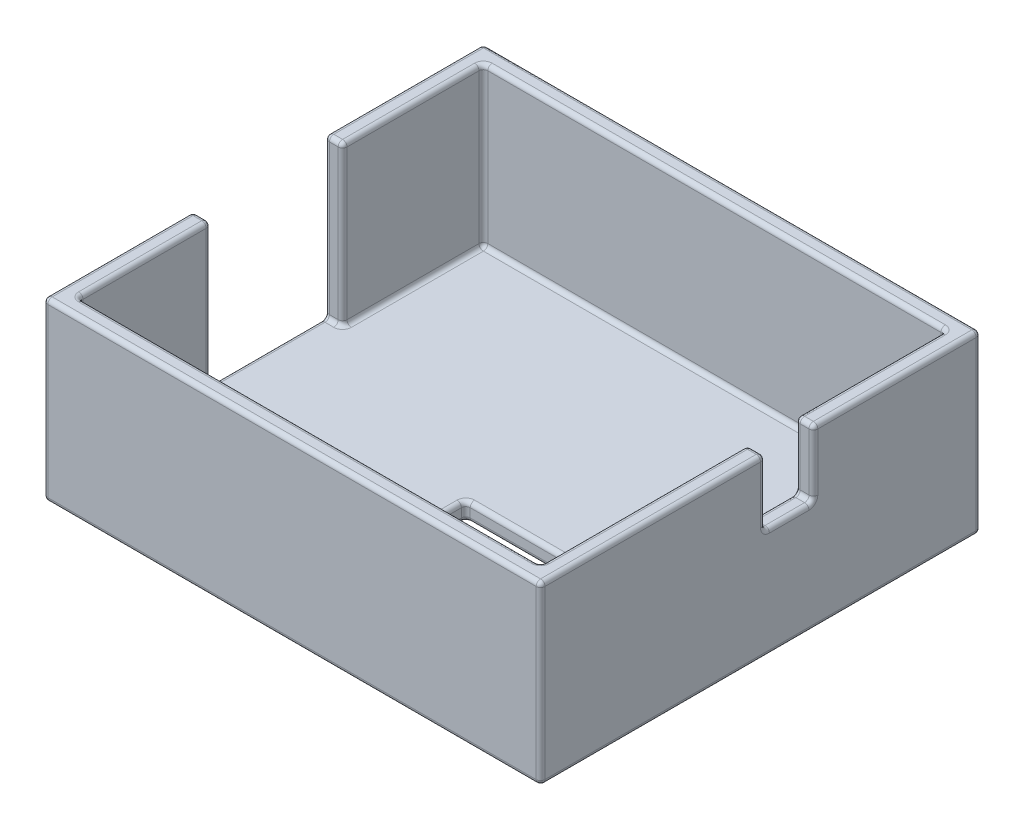
SolidWorks part; units mm, degrees
ref_plane "Front Plane" through (0, 0, 0) normal (0, 0, 1) x (1, 0, 0)
ref_plane "Top Plane" through (0, 0, 0) normal (0, 1, 0) x (1, 0, 0)
ref_plane "Right Plane" through (0, 0, 0) normal (1, 0, 0) x (0, 0, -1)
sketch "Sketch1" plane through (0, 0, 0) normal (0, 1, 0) x (1, 0, 0)
  line L1 (0, 100) -> (113, 100)
  line L2 (0, 100) -> (0, 0)
  line L3 (0, 0) -> (113, 0)
  line L4 (113, 100) -> (113, 0)
  line L5 (4, 96) -> (109, 96) construction
  line L6 (4, 96) -> (4, 4) construction
  line L7 (4, 4) -> (109, 4) construction
  line L8 (109, 96) -> (109, 4) construction
  dimension "D1" = 4
  dimension "D2" = 4
  dimension "D3" = 4
  dimension "D4" = 4
  dimension "D5" = 92
  dimension "105" = 105
extrude "Boss-Extrude1" add sketch "Sketch1" along normal blind 4
sketch "Sketch2" plane through (0, 4, 0) normal (0, 1, 0) x (1, 0, 0)
  line L0 (113, 100) -> (0, 100) construction
  line L1 (4, 96) -> (109, 96)
  line L2 (4, 96) -> (4, 4)
  line L3 (4, 4) -> (109, 4)
  line L4 (109, 96) -> (109, 4)
  line L5 (0, 0) -> (113, 0) construction
  line L6 (0, 100) -> (0, 0) construction
  line L7 (113, 0) -> (113, 100) construction
  line L9 (0, 100) -> (113, 100)
  line L10 (0, 100) -> (0, 0)
  line L11 (0, 0) -> (113, 0)
  line L12 (113, 100) -> (113, 0)
  dimension "D1" = 4
  dimension "D2" = 4
  dimension "D3" = 4
  dimension "D4" = 4
extrude "Boss-Extrude2" add sketch "Sketch2" along normal blind 36
sketch "Sketch3" plane through (4, 0, 0) normal (1, 0, 0) x (0, 0, -1)
  line L0 (64, 40) -> (64, 4)
  line L1 (96, 40) -> (4, 40) construction
  line L2 (64, 4) -> (34, 4)
  line L3 (34, 4) -> (34, 40)
  line L4 (34, 40) -> (64, 40)
  line L5 (96, 40) -> (96, 4) construction
  line L6 (4, 40) -> (4, 4) construction
  line L7 (96, 4) -> (4, 4) construction
  dimension "D1" = 32
  dimension "D2" = 30
extrude "Cut-Extrude1" cut sketch "Sketch3" against normal blind 40
sketch "Sketch4" plane through (109, 0, 0) normal (-1, 0, 0) x (0, 0, 1)
  line L0 (-4, 40) -> (-96, 40) construction
  line L1 (-62, 40) -> (-51, 40)
  line L2 (-62, 40) -> (-62, 25)
  line L3 (-62, 25) -> (-51, 25)
  line L4 (-51, 40) -> (-51, 25)
  line L5 (-96, 40) -> (-96, 4) construction
  line L6 (-4, 40) -> (-4, 4) construction
  dimension "D1" = 34
  dimension "D2" = 47
  dimension "D3" = 15
extrude "Cut-Extrude2" cut sketch "Sketch4" against normal blind 40
sketch "Sketch5" plane through (0, 0, 0) normal (0, -1, 0) x (1, 0, 0)
  line L0 (0, -100) -> (0, 0) construction
  line L1 (52, -13) -> (95, -13)
  line L2 (52, -13) -> (52, -44)
  line L3 (52, -44) -> (95, -44)
  line L4 (95, -13) -> (95, -44)
  line L5 (113, 0) -> (113, -100) construction
  line L6 (113, -100) -> (0, -100) construction
  line L7 (0, 0) -> (113, 0) construction
  dimension "D1" = 52
  dimension "D2" = 18
  dimension "D3" = 56
  dimension "D4" = 13
extrude "Cut-Extrude3" cut sketch "Sketch5" against normal blind 40
fillet "Fillet1" radius 1 60 edges at (52, 4, -28.5) (73.5, 4, -13) (95, 4, -28.5) (73.5, 4, -44) (0, 20, 0) (113, 20, 0) (113, 20, -100) (0, 20, -100) (56.5, 0, -100) (113, 0, -50) (56.5, 0, 0) (0, 0, -50) (56.5, 40, -100) (113, 40, -25.5) (113, 40, -81) (56.5, 40, 0) (0, 40, -82) (0, 40, -17) (4, 22, -4) (109, 22, -4) (109, 22, -96) (4, 22, -96) (56.5, 40, -96) (109, 40, -27.5) (109, 40, -79) (56.5, 40, -4) (4, 40, -80) (4, 40, -19) (56.5, 4, -96) (109, 4, -50) (56.5, 4, -4) (4, 4, -80) (4, 4, -19) (0, 22, -64) (0, 4, -49) (0, 22, -34) (2, 40, -64) (2, 4, -64) (2, 4, -34) (2, 40, -34) (4, 22, -64) (4, 22, -34) (113, 32.5, -62) (113, 32.5, -51) (113, 25, -56.5) (111, 40, -62) (111, 40, -51) (111, 25, -51) (111, 25, -62) (109, 32.5, -51) (109, 25, -56.5) (109, 32.5, -62) (52, 2, -13) (95, 2, -13) (95, 2, -44) (52, 2, -44) (73.5, 0, -13) (95, 0, -28.5) (73.5, 0, -44) (52, 0, -28.5)
